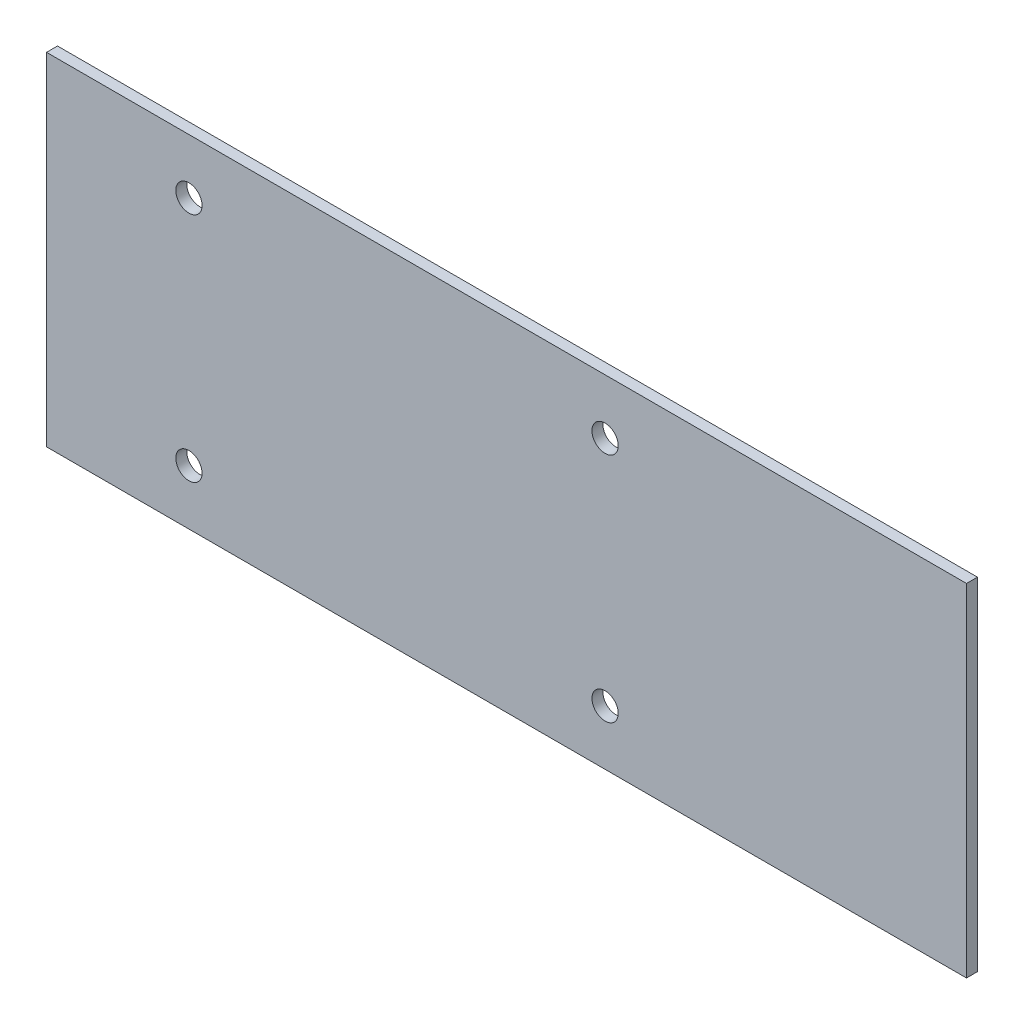
SolidWorks part; units mm, degrees
material "Plain Carbon Steel"
ref_plane "Front Plane" through (0, 0, 0) normal (0, 0, 1) x (1, 0, 0)
ref_plane "Top Plane" through (0, 0, 0) normal (0, 1, 0) x (1, 0, 0)
ref_plane "Right Plane" through (0, 0, 0) normal (1, 0, 0) x (0, 0, -1)
sketch "Sketch1" plane through (0, 0, 0) normal (0, 0, 1) x (1, 0, 0)
  line L0 (55, 0) -> (-55, 0) construction
  line L1 (-355, 52.92) -> (-165, 52.92) construction
  line L2 (-355, 52.92) -> (-355, -52.92) construction
  line L3 (-355, -52.92) -> (-165, -52.92) construction
  line L4 (-165, 52.92) -> (-165, -52.92) construction
  line L5 (0, -55) -> (0, 55) construction
  line L7 (0, -78) -> (-420, -78)
  line L8 (0, -78) -> (0, 78)
  line L9 (0, 78) -> (-420, 78)
  line L10 (-420, -78) -> (-420, 78)
  circle A0 centre (-355, 52.92) radius 6
  circle A1 centre (-165, 52.92) radius 6
  circle A2 centre (-165, -52.92) radius 6
  circle A3 centre (-355, -52.92) radius 6
  point P4 (-355, 0)
  point P14 (0, 0)
  dimension "D3" = 12
  dimension "D1" = 105.84
  dimension "D2" = 190
  dimension "D4" = 420
  dimension "D5" = 156
  dimension "D6" = 65
  dimension "D7" = 78
extrude "Boss-Extrude1" add sketch "Sketch1" along normal blind 5
